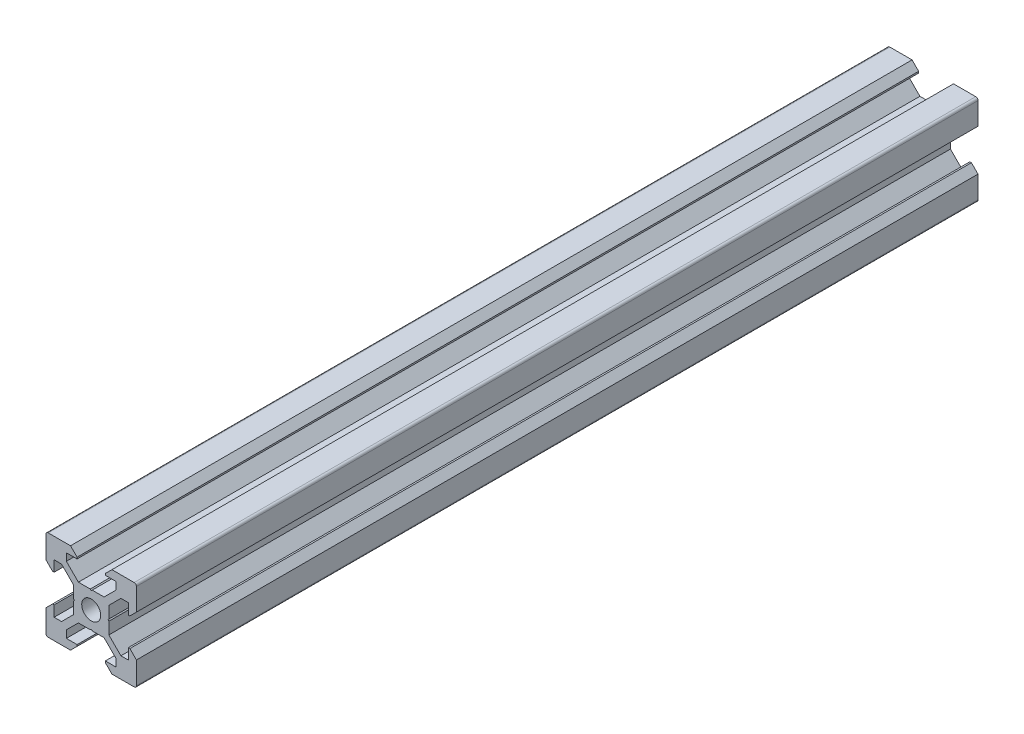
SolidWorks part; units mm, degrees
material "6061-T6 (SS)"
ref_plane "Front Plane" through (0, 0, 0) normal (0, 0, 1) x (1, 0, 0)
ref_plane "Top Plane" through (0, 0, 0) normal (0, 1, 0) x (1, 0, 0)
ref_plane "Right Plane" through (0, 0, 0) normal (1, 0, 0) x (0, 0, -1)
sketch "Sketch1" plane through (0, 0, 0) normal (0, 0, 1) x (1, 0, 0)
  line L1 (9.5, -10) -> (-9.5, -10)
  line L2 (10, -9.5) -> (10, 9.5)
  line L3 (9.5, 10) -> (-9.5, 10)
  line L4 (-10, -9.5) -> (-10, 9.5)
  line L5 (10, -10) -> (-10, 10) construction
  line L6 (10, 10) -> (-10, -10) construction
  circle A0 centre (0, 0) radius 2.1
  arc A1 (-9.5, 10) -> (-10, 9.5) centre (-9.5, 9.5) ccw
  arc A2 (10, 9.5) -> (9.5, 10) centre (9.5, 9.5) ccw
  arc A3 (9.5, -10) -> (10, -9.5) centre (9.5, -9.5) ccw
  arc A4 (-9.5, -10) -> (-10, -9.5) centre (-9.5, -9.5) cw
  point P0 (0, 0)
  line B0 (0, 0) -> (0, 10) construction
  line B1 (0, 3.69) -> (-0.21, 3.9)
  line B2 (-0.21, 3.9) -> (-2.8393, 3.9)
  line B3 (-2.8393, 3.9) -> (-5.5, 6.5607)
  line B4 (-5.5, 6.5607) -> (-5.5, 8.2)
  line B5 (-5.5, 8.2) -> (-3.125, 8.2)
  line B6 (-3.125, 8.2) -> (-3.125, 8.545)
  line B7 (-3.125, 8.545) -> (-4.58, 10)
  line B8 (-4.58, 10) -> (4.58, 10)
  line B9 (0, 0) -> (-5.9132, 5.9132) construction
  line B10 (3.125, 8.545) -> (4.58, 10)
  line B11 (3.125, 8.2) -> (3.125, 8.545)
  line B12 (5.5, 8.2) -> (3.125, 8.2)
  line B13 (5.5, 6.5607) -> (5.5, 8.2)
  line B14 (2.8393, 3.9) -> (5.5, 6.5607)
  line B15 (0.21, 3.9) -> (2.8393, 3.9)
  line B16 (0, 3.69) -> (0.21, 3.9)
  line B17 (0, 0) -> (-10, 0) construction
  line B18 (-3.69, 0) -> (-3.9, -0.21)
  line B19 (-3.9, -0.21) -> (-3.9, -2.8393)
  line B20 (-3.9, -2.8393) -> (-6.5607, -5.5)
  line B21 (-6.5607, -5.5) -> (-8.2, -5.5)
  line B22 (-8.2, -5.5) -> (-8.2, -3.125)
  line B23 (-8.2, -3.125) -> (-8.545, -3.125)
  line B24 (-8.545, -3.125) -> (-10, -4.58)
  line B25 (-10, -4.58) -> (-10, 4.58)
  line B26 (0, 0) -> (-5.9132, -5.9132) construction
  line B27 (-8.545, 3.125) -> (-10, 4.58)
  line B28 (-8.2, 3.125) -> (-8.545, 3.125)
  line B29 (-8.2, 5.5) -> (-8.2, 3.125)
  line B30 (-6.5607, 5.5) -> (-8.2, 5.5)
  line B31 (-3.9, 2.8393) -> (-6.5607, 5.5)
  line B32 (-3.9, 0.21) -> (-3.9, 2.8393)
  line B33 (-3.69, 0) -> (-3.9, 0.21)
  line B34 (0, 0) -> (0, -10) construction
  line B35 (0, -3.69) -> (0.21, -3.9)
  line B36 (0.21, -3.9) -> (2.8393, -3.9)
  line B37 (2.8393, -3.9) -> (5.5, -6.5607)
  line B38 (5.5, -6.5607) -> (5.5, -8.2)
  line B39 (5.5, -8.2) -> (3.125, -8.2)
  line B40 (3.125, -8.2) -> (3.125, -8.545)
  line B41 (3.125, -8.545) -> (4.58, -10)
  line B42 (4.58, -10) -> (-4.58, -10)
  line B43 (0, 0) -> (5.9132, -5.9132) construction
  line B44 (-3.125, -8.545) -> (-4.58, -10)
  line B45 (-3.125, -8.2) -> (-3.125, -8.545)
  line B46 (-5.5, -8.2) -> (-3.125, -8.2)
  line B47 (-5.5, -6.5607) -> (-5.5, -8.2)
  line B48 (-2.8393, -3.9) -> (-5.5, -6.5607)
  line B49 (-0.21, -3.9) -> (-2.8393, -3.9)
  line B50 (0, -3.69) -> (-0.21, -3.9)
  line B51 (0, 0) -> (10, 0) construction
  line B52 (3.69, 0) -> (3.9, 0.21)
  line B53 (3.9, 0.21) -> (3.9, 2.8393)
  line B54 (3.9, 2.8393) -> (6.5607, 5.5)
  line B55 (6.5607, 5.5) -> (8.2, 5.5)
  line B56 (8.2, 5.5) -> (8.2, 3.125)
  line B57 (8.2, 3.125) -> (8.545, 3.125)
  line B58 (8.545, 3.125) -> (10, 4.58)
  line B59 (10, 4.58) -> (10, -4.58)
  line B60 (0, 0) -> (5.9132, 5.9132) construction
  line B61 (8.545, -3.125) -> (10, -4.58)
  line B62 (8.2, -3.125) -> (8.545, -3.125)
  line B63 (8.2, -5.5) -> (8.2, -3.125)
  line B64 (6.5607, -5.5) -> (8.2, -5.5)
  line B65 (3.9, -2.8393) -> (6.5607, -5.5)
  line B66 (3.9, -0.21) -> (3.9, -2.8393)
  line B67 (3.69, 0) -> (3.9, -0.21)
  dimension "D1" = 4.2
  dimension "D3" = 0.5
  dimension "D2" = 20
sketch_block_instance "V Slot 1-4"
sketch_block "V Slot 1" parameters "D1"=10, "D2"=11, "D3"=4.3, "D4"=1.8, "D5"=0.21, "D6"=45, "D7"=9.16, "D8"=1.5, "D9"=6.25
sketch_block_instance "V Slot 1-5"
sketch_block_instance "V Slot 1-6"
sketch_block_instance "V Slot 1-7"
extrude "Boss-Extrude1" add sketch "Sketch1" along normal mid plane 186.1 contours B67 B52 B53 B54 B55 B56 B57 B58 L2 A2 L3 B10 B11 B12 B13 B14 B15 B16 B1 B2 B3 B4 B5 B6 B7 A1 L4 B27 B28 B29 B30 B31 B32 B33 B18 B19 B20 B21 B22 B23 B24 A4 L1 B44 B45 B46 B47 B48 B49
